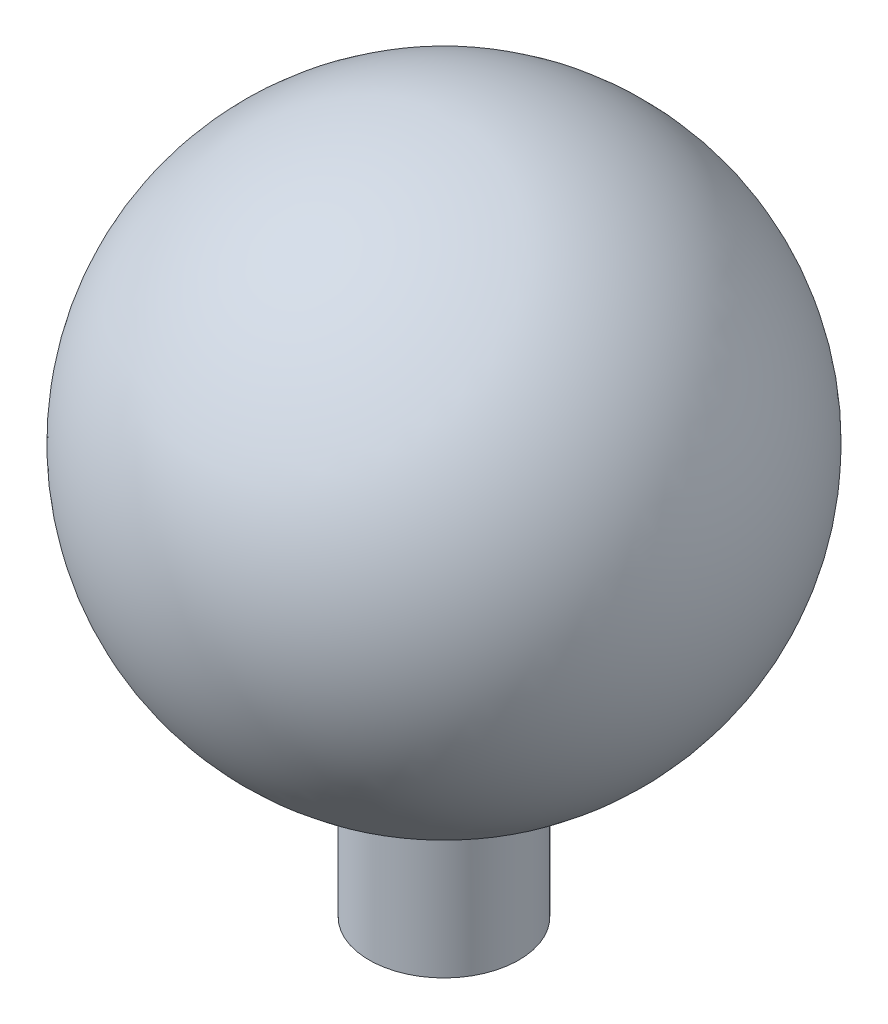
SolidWorks part; units mm, degrees
ref_plane "Front Plane" through (0, 0, 0) normal (0, 0, 1) x (1, 0, 0)
ref_plane "Top Plane" through (0, 0, 0) normal (0, 1, 0) x (1, 0, 0)
ref_plane "Right Plane" through (0, 0, 0) normal (1, 0, 0) x (0, 0, -1)
sketch "Sketch2" plane through (0, 0, 0) normal (0, 0, 1) x (1, 0, 0)
  line L0 (0, 0) -> (0, 17.2633)
  line L2 (-10, 0) -> (-10, 18.6213)
  line L3 (0, 17.2633) -> (0, 92.2633)
  line L4 (0, 0) -> (-10, 0)
  arc A0 (0, 92.2633) -> (-10, 18.6213) centre (0, 54.7633) ccw
  dimension "D1" = 75
  dimension "D2" = 17.2633
revolve "Revolve1" add sketch "Sketch2" angle 360 about L0
ref_point "Point1"
